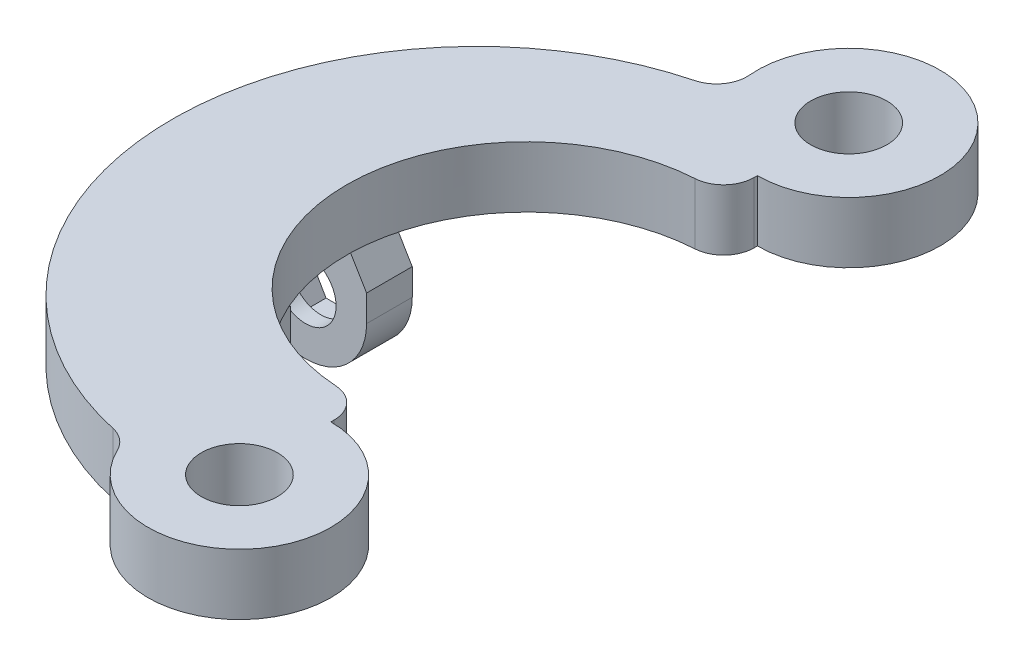
SolidWorks part; units mm, degrees
ref_plane "Front Plane" through (0, 0, 0) normal (0, 0, 1) x (1, 0, 0)
ref_plane "Top Plane" through (0, 0, 0) normal (0, 1, 0) x (1, 0, 0)
ref_plane "Right Plane" through (0, 0, 0) normal (1, 0, 0) x (0, 0, -1)
ref_plane "Plane1" through (0, 5.7709, 0) normal (0, 1, 0) x (1, 0, 0)
sketch "Sketch1" plane through (0, 5.7709, 0) normal (0, 1, 0) x (1, 0, 0)
  line L0 (7, -23.7589) -> (7, 4.2411)
  arc A0 (1.2527, -31.4817) -> (7, -23.7589) centre (7, -29.7589) ccw
  arc A1 (7, 4.2411) -> (1.4384, 7.9897) centre (7, 10.2411) ccw
  arc A2 (1.4384, 7.9897) -> (1.2527, -31.4817) centre (4.5849, -11.7613) ccw
extrude "Boss-Extrude1" add sketch "Sketch1" against normal blind 4
ref_plane "Plane2" through (0, 0, 17.5) normal (0, 0, 1) x (1, 0, 0)
sketch "Sketch2" plane through (0, 0, 17.5) normal (0, 0, 1) x (1, 0, 0)
  line L0 (-4.9131, -1.6605) -> (-4.9131, 1.7709)
  line L1 (-12.9131, 1.7709) -> (-12.9131, -1.6605)
  arc A0 (-12.9131, -1.6605) -> (-4.9131, -1.6605) centre (-8.9131, -1.6605) ccw
  spline S0 degree 1 poles (-12.9131, 1.7709) (-4.9131, 1.7709) knots 0 0 1 1
extrude "Boss-Extrude2" add sketch "Sketch2" against normal blind 3
ref_plane "Plane3" through (0, 0, 9.5) normal (0, 0, 1) x (1, 0, 0)
sketch "Sketch3" plane through (0, 0, 9.5) normal (0, 0, 1) x (1, 0, 0)
  line L0 (-4.9131, -1.7291) -> (-4.9131, 0.0113)
  line L1 (-4.9131, 0.0113) -> (-5.9622, 1.7709)
  line L2 (-12.9131, 1.7709) -> (-12.9131, -1.7291)
  arc A0 (-12.9131, -1.7291) -> (-4.9131, -1.7291) centre (-8.9131, -1.7291) ccw
  spline S0 degree 1 poles (-12.9131, 1.7709) (-5.9622, 1.7709) knots 0 0 1 1
extrude "Boss-Extrude3" add sketch "Sketch3" against normal blind 3
sketch "Sketch4" plane through (0, 0, 6.5) normal (0, 0, -1) x (-1, 0, 0)
  line L0 (7.2532, 1.1459) -> (5.5933, -1.7291)
  line L1 (5.5933, -1.7291) -> (7.2532, -4.6041)
  line L2 (7.2532, -4.6041) -> (10.5729, -4.6041)
  line L3 (10.5729, -4.6041) -> (12.2328, -1.7291)
  line L4 (12.2328, -1.7291) -> (10.5729, 1.1459)
  line L5 (10.5729, 1.1459) -> (7.2532, 1.1459)
extrude "Cut-Extrude1" cut sketch "Sketch4" against normal blind 2
hole_wizard "Ø5.0 (5) Diameter Hole1" positions "Sketch6" profile "Sketch5" hole size "Ø5.0" standard "ANSI Metric"
sketch "Sketch6" plane through (0, 5.7709, 0) normal (0, 1, 0) x (1, 0, 0)
  point P0 (7, -29.7589)
  point P1 (7, 10.2411)
sketch "Sketch5" plane through (7, 5.7709, 29.7589) normal (1, 0, 0) x (0, 0, 1)
  line L0 (0, 0) -> (0, 11.5)
  line L1 (0, 11.5) -> (2.5, 11.5)
  line L2 (2.5, 11.5) -> (2.5, 0)
  line L5 (2.5, 0) -> (0, 0)
  line L11 (0, -6.35) -> (0, 107.95) construction
  dimension "Thru Hole Dia." = 5
  dimension "Thru Hole Depth" = 11.5
hole_wizard "Ø4.0 (4) Diameter Hole1" positions "Sketch8" profile "Sketch7" hole size "Ø4.0" standard "ANSI Metric"
sketch "Sketch8" plane through (0, 0, 14.5) normal (0, 0, -1) x (-1, 0, 0)
  point P0 (8.9131, -1.7291)
sketch "Sketch7" plane through (-8.9131, -1.7291, 14.5) normal (1, 0, 0) x (0, 1, 0)
  line L0 (0, 0) -> (0, 21.2589)
  line L1 (0, 21.2589) -> (2, 21.2589)
  line L2 (2, 21.2589) -> (2, 0)
  line L5 (2, 0) -> (0, 0)
  line L11 (0, -6.35) -> (0, 107.95) construction
  dimension "Thru Hole Dia." = 4
  dimension "Thru Hole Depth" = 21.2589
hole_wizard "M20 Clearance Hole1" positions "Sketch10" profile "Sketch9" hole size "M20" standard "ANSI Metric"
sketch "Sketch10" plane through (0, 5.7709, 0) normal (0, 1, 0) x (1, 0, 0)
  point P0 (5.8441, -9.7589)
sketch "Sketch9" plane through (5.8441, 5.7709, 9.7589) normal (1, 0, 0) x (0, 0, 1)
  line L0 (0, 0) -> (0, 4)
  line L1 (0, 4) -> (11.8092, 4)
  line L2 (11.8092, 4) -> (11.8092, 0)
  line L5 (11.8092, 0) -> (0, 0)
  line L10 (0, 4) -> (-11.8092, 4) construction
  line L11 (0, -6.35) -> (0, 107.95) construction
  dimension "Hole Dia." = 23.6183
  dimension "Hole Depth" = 4
  dimension "Drill Angle" = 180
hole_wizard "Ø4.0 (4) Diameter Hole2" positions "Sketch12" profile "Sketch11" hole size "Ø4.0" standard "ANSI Metric"
sketch "Sketch12" plane through (0, 0, 8.5) normal (0, 0, -1) x (-1, 0, 0)
  point P0 (8.9131, -1.7291)
sketch "Sketch11" plane through (-8.9131, -1.7291, 8.5) normal (1, 0, 0) x (0, 1, 0)
  line L0 (0, 0) -> (0, 27.2589)
  line L1 (0, 27.2589) -> (2, 27.2589)
  line L2 (2, 27.2589) -> (2, 0)
  line L5 (2, 0) -> (0, 0)
  line L11 (0, -6.35) -> (0, 107.95) construction
  dimension "Thru Hole Dia." = 4
  dimension "Thru Hole Depth" = 27.2589
fillet "Fillet1" radius 2 4 edges at (1.2527, 3.7709, 31.4817) (1.4384, 3.7709, -7.9897) (7, 3.7709, -1.9936) (7, 3.7709, 21.5113)
ref_plane "Plane4" through (0, 0, 12) normal (0, 0, 1) x (1, 0, 0)
